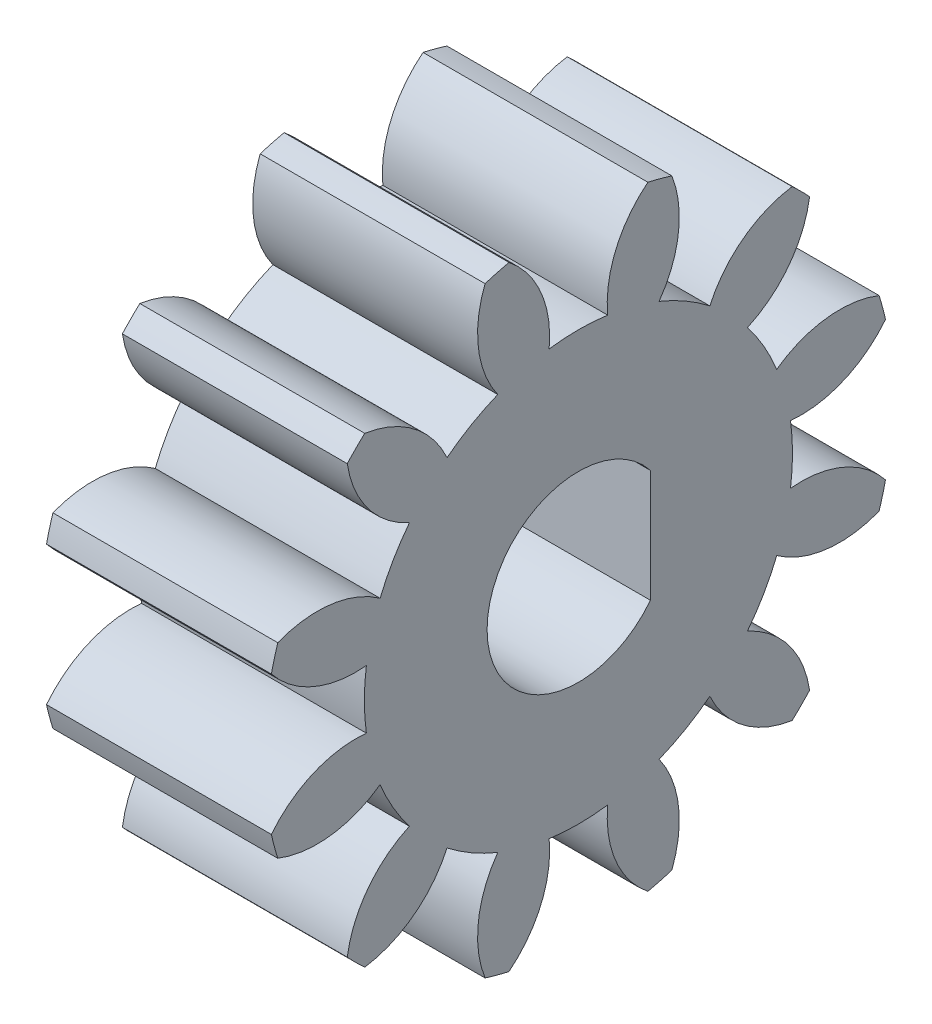
SolidWorks part; units mm, degrees
ref_plane "Plane1" through (0, 0, 0) normal (0, 0, 1) x (1, 0, 0)
ref_plane "Plane2" through (0, 0, 0) normal (0, 1, 0) x (1, 0, 0)
ref_plane "Plane3" through (0, 0, 0) normal (1, 0, 0) x (0, 0, -1)
sketch "HoldingSke" plane through (0, 0, 0) normal (0, 1, 0) x (1, 0, 0)
  line L0 (0, 0) -> (496.899, -105.6191)
  line L1 (-15, 0) -> (100, 0) construction
  line L2 (0, 0) -> (-2.1039, 2.3779)
  line L3 (0, 0) -> (-11.863, 4.5341)
  line L4 (0, 0) -> (8.4473, 1.7955)
  line L5 (0, 0) -> (-47.5972, -17.7524)
  line L6 (0, 0) -> (-5.2639, -3.5516)
  line L7 (-2.1039, 2.3779) -> (8.8308, 51.9871)
  line L8 (-76.2, 54.61) -> (-72.771, 54.61)
  line L9 (-67.7845, 28.3722) -> (-49.3413, 33.142)
  line L10 (-76.2, 71.12) -> (104.1128, 71.12)
  line L11 (0, 0) -> (-6.35, 0)
  line L12 (-76.2, 101.6) -> (-76.1492, 101.6)
  line L13 (24.9733, 27.94) -> (52.9518, 28.4284)
  line L14 (24.9733, 27.94) -> (25.0241, 27.9398)
  line L15 (24.9733, 27.94) -> (100.4021, 29.52)
  circle A0 centre (0, 0) radius 1.5875
  circle A1 centre (0, 0) radius 6.0452
  circle A2 centre (0, 0) radius 38.1
  circle A3 centre (0, 0) radius 1.5875
  dimension "MHD" = 12.0904
  dimension "Hub_dia" = 76.2
  dimension "Bore" = 3.175
  dimension "MBD" = 3.175
  dimension "Num_teeth" = 12
  dimension "Pitch" = 508
  dimension "Overall_len" = 50.8
  dimension "Show_teeth" = 12
  dimension "Thickness" = 6.35
  dimension "OAL" = 50.8001
  dimension "T_dim" = 3.429
  dimension "Ap" = 14.5
  dimension "H" = 19.05
  dimension "Pitch_radius" = 180.3128
  dimension "Width" = 6.35
  dimension "Backlash" = 0.0508
  dimension "Addendum_fac" = 1
  dimension "Dedendum_fac" = 1.2
  dimension "Clearance_fac" = 0.2
  dimension "Dedendum_add" = 0.0508
sketch "BasProSke" plane through (0, 0, 0) normal (0, 1, 0) x (1, 0, 0)
  line L0 (-10, 0) -> (60, 0) construction
  line L1 (0, 0) -> (0, 8.89)
  line L2 (0, 0) -> (6.35, 0)
  line L3 (6.35, 0) -> (6.35, 8.89)
  line L4 (6.35, 8.89) -> (0, 8.89)
  dimension "Thickness" = 6.35
  dimension "Diameter" = 17.78
revolve "Base-Revolve" add sketch "BasProSke" angle 360 about L0
sketch "TooCutSke" plane through (0, 0, 0) normal (1, 0, 0) x (0, 0, -1)
  line L1 (0, 0) -> (0, 107) construction
  line L2 (0, 0) -> (-1.0834, 7.5426) construction
  line L3 (0, 0) -> (-3.9164, 14.6164) construction
  line L4 (-1.0834, 7.5426) -> (-1.9582, 7.3082) construction
  arc A0 (0.8272, 5.9883) -> (-0.8272, 5.9883) centre (0, 0) ccw
  arc A1 (1.9874, 8.6911) -> (-1.9874, 8.6911) centre (0, 0) ccw
  circle A2 centre (0, 0) radius 7.62 construction
  circle A3 centre (0, 0) radius 7.3773 construction
  arc A4 (-0.8272, 5.9883) -> (-1.9874, 8.6911) centre (-3.8605, 6.2865) ccw
  arc A5 (1.9874, 8.6911) -> (0.8272, 5.9883) centre (3.8605, 6.2865) ccw
  dimension "Root_dia" = 12.0904
  dimension "Overcut_dia" = 17.8308
  dimension "Pitch_dia" = 15.24
  dimension "Base_dia" = 14.7546
  dimension "Flank_rad" = 3.048
  dimension "Half_ang" = 15
  dimension "Half_CT" = 0.9057
extrude "ToothCut" cut sketch "TooCutSke" along normal through all
fillet "Breaks" [suppressed] radius 0.0254
fillet "RootFillets" [suppressed] radius 0.3048
pattern_circular "TeethCuts" count 12 every 30 about axis through (-10, 0, 0) along (1, 0, 0) of "ToothCut", "RootFillets", "Breaks"
sketch "HubNeaOneSke" plane through (0, 0, 0) normal (-1, 0, 0) x (0, 0, 1)
  circle A0 centre (0, 0) radius 6.0452
  dimension "Diameter" = 12.0904
extrude "HubNearOne" [suppressed] add sketch "HubNeaOneSke" along normal blind 44.4501
sketch "HubNeaBotSke" plane through (0, 0, 0) normal (-1, 0, 0) x (0, 0, 1)
  circle A0 centre (0, 0) radius 6.0452
  dimension "Diameter" = 12.0904
extrude "HubNearBoth" [suppressed] add sketch "HubNeaBotSke" along normal blind 22.225
ref_plane "FarPln" through (6.35, 0, 0) normal (1, 0, 0) x (0, 0, -1)
sketch "HubFarSke" plane through (6.35, 0, 0) normal (1, 0, 0) x (0, 0, -1)
  circle A0 centre (0, 0) radius 6.0452
  dimension "Diameter" = 12.0904
extrude "HubFar" [suppressed] add sketch "HubFarSke" along normal blind 22.225
sketch "BorSke" plane through (0, 0, 0) normal (1, 0, 0) x (0, 0, -1)
  circle A0 centre (0, 0) radius 1.5875
  dimension "Diameter" = 3.175
extrude "Bore" cut sketch "BorSke" along normal mid plane 101.6001
sketch "KeySke" plane through (0, 0, 0) normal (1, 0, 0) x (0, 0, -1)
  line L0 (-0.127, 0) -> (-0.127, 1.8415)
  line L1 (-0.127, 1.8415) -> (0.127, 1.8415)
  line L2 (0.127, 1.8415) -> (0.127, 0)
  line L3 (0, 0) -> (0, 34) construction
  line L4 (-0.127, 0) -> (0.127, 0)
  dimension "Offset" = 1.8415
  dimension "Width" = 0.254
extrude "Keyway" [suppressed] cut sketch "KeySke" along normal mid plane 101.6001
pattern_circular "Keyway2" [suppressed] count 2 every 90 about axis through (-10, 0, 0) along (1, 0, 0)
sketch "Sketch1" plane through (6.35, 0, 0) normal (1, 0, 0) x (0, 0, -1)
  line L0 (2.5797, 0) -> (3.2579, 0) construction
  line L1 (3.2579, -1.5875) -> (3.2579, 1.5875) construction
  line L2 (3.2579, 1.5875) -> (2.0334, 1.5875) construction
  line L3 (2.0334, 1.5875) -> (2.0334, -1.5875)
  circle A0 centre (0, 0) radius 2.5797
  point P8 (3.2579, 0)
  circle M5 centre (0, 0) radius 1.5875
  dimension "D1" = 5.1594
  dimension "D2" = 3.175
extrude "Cut-Extrude1" cut sketch "Sketch1" against normal through all contours L3 A0 M5
equation "' \"Pitch@HoldingSke\" = 4"
equation "' \"Num_teeth@HoldingSke\" = 12"
equation "' \"Ap@HoldingSke\" =  20"
equation "' \"Ap@HoldingSke\" = 20"
equation "' \"Width@HoldingSke\" = 0.5"
equation "' \"Hub_dia@HoldingSke\"= 1"
equation "' \"Hub_dia@HoldingSke\" = 1"
equation "' \"Overall_len@HoldingSke\" = 1.0"
equation "' \"Bore@HoldingSke\" = 0.75"
equation "' \"T_dim@HoldingSke\" = 0.85"
equation "' \"Width@KeySke\" = 0.25"
equation "' \"Show_teeth@HoldingSke\" = 13"
equation "' \"Backlash@HoldingSke\" = 0.009"
equation "' \"Addendum_fac@HoldingSke\" = 1.0"
equation "' \"Dedendum_fac@HoldingSke\" = 1.25"
equation "' \"Dedendum_add@HoldingSke\" = 0.00005"
equation "' \"Clearance_fac@HoldingSke\" = 0.25"
equation "' \"Pitch@HoldingSke\" = 0.5"
equation "' \"Num_teeth@HoldingSke\" = 23"
equation "' \"Show_teeth@HoldingSke\" = 23"
equation "' \"Backlash@HoldingSke\" = 0.0375"
equation "\"Overcut_dia@TooCutSke\" = (\"Num_teeth@HoldingSke\" + 2 * \"Addendum_fac@HoldingSke\") / \"Pitch@HoldingSke\" + 0.002"
equation "\"Pitch_dia@TooCutSke\" = \"Num_teeth@HoldingSke\" / \"Pitch@HoldingSke\""
equation "\"Base_dia@TooCutSke\" = \"Num_teeth@HoldingSke\" / \"Pitch@HoldingSke\" * cos((\"Ap@HoldingSke\"  * 3.14159265 / 180))"
equation "\"Root_dia@TooCutSke\" = (\"Num_teeth@HoldingSke\" + 2) / \"Pitch@HoldingSke\" - 2 * (\"Addendum_fac@HoldingSke\" + \"Dedendum_fac@HoldingSke\") / \"Pitch@HoldingSke\" - \"Dedendum_add@HoldingSke\" * 2"
equation "\"Half_ang@TooCutSke\" = 180 / \"Num_teeth@HoldingSke\""
equation "\"Half_CT@TooCutSke\" = \"Num_teeth@HoldingSke\" / \"Pitch@HoldingSke\" * sin((3.14159265 / 2 / \"Num_teeth@HoldingSke\")) / 2 - 7 * \"Backlash@HoldingSke\" / 4"
equation "\"Flank_rad@TooCutSke\" = \"Num_teeth@HoldingSke\" / \"Pitch@HoldingSke\" / 5"
equation "\"Radius@RootFillets\" = \"Clearance_fac@HoldingSke\" / \"Pitch@HoldingSke\" + \"Dedendum_add@HoldingSke\""
equation "\"Break_rad@Breaks\" = 0.02 / \"Pitch@HoldingSke\""
equation "\"Thickness@HoldingSke\" = \"Width@HoldingSke\""
equation "\"OAL@HoldingSke\" = \"Thickness@HoldingSke\""
equation "\"MHD@HoldingSke\" = (\"Num_teeth@HoldingSke\" + 2) / \"Pitch@HoldingSke\" - 2 * (\"Addendum_fac@HoldingSke\" + \"Dedendum_fac@HoldingSke\")  / \"Pitch@HoldingSke\" - \"Dedendum_add@HoldingSke\" * 2"
equation "\"MBD@HoldingSke\" = (\"Num_teeth@HoldingSke\" + 2) / \"Pitch@HoldingSke\" - 2 * (\"Addendum_fac@HoldingSke\" + \"Dedendum_fac@HoldingSke\")  / \"Pitch@HoldingSke\" - \"Dedendum_add@HoldingSke\" * 2 - 0.002"
equation "\"MHD@HoldingSke\" = ((sgn( \"MHD@HoldingSke\" - \"Hub_dia@HoldingSke\" )-1)*( \"MHD@HoldingSke\" - \"Hub_dia@HoldingSke\" ))/-2+ \"Hub_dia@HoldingSke\""
equation "\"MBD@HoldingSke\" = ((sgn( \"MBD@HoldingSke\" - \"Bore@HoldingSke\" )-1)*( \"MBD@HoldingSke\" - \"Bore@HoldingSke\" ))/-2+ \"Bore@HoldingSke\""
equation "\"OAL@HoldingSke\" = ((sgn( \"OAL@HoldingSke\" - \"Overall_len@HoldingSke\" )+1)*( \"OAL@HoldingSke\" - \"Overall_len@HoldingSke\" ))/2 + \"Overall_len@HoldingSke\" + 0.000002"
equation "\"Num_teeth@TeethCuts\" = int( \"Show_teeth@HoldingSke\" ) + 1"
equation "\"Num_teeth@TeethCuts\" = ((sgn( \"Num_teeth@TeethCuts\" - \"Num_teeth@HoldingSke\" )-1)*( \"Num_teeth@TeethCuts\" - \"Num_teeth@HoldingSke\" ))/-2+ \"Num_teeth@HoldingSke\""
equation "\"Num_teeth@TeethCuts\" = ((sgn( \"Num_teeth@TeethCuts\" - 2.0)+1)*( \"Num_teeth@TeethCuts\" - 2.0))/2 +2.0"
equation "\"Angle@TeethCuts\" = 360.0 / \"Num_teeth@HoldingSke\""
equation "\"Diameter@BasProSke\" = (\"Num_teeth@HoldingSke\" + 2 * \"Addendum_fac@HoldingSke\") / \"Pitch@HoldingSke\""
equation "\"Thickness@BasProSke\"  = \"Thickness@HoldingSke\""
equation "' \"Fillet_rad@BasProSke\" =  \"Thickness@HoldingSke\" * 0.05"
equation "' \"Fillet_rad@BasProSke\" = \"Thickness@HoldingSke\" * 0.05"
equation "\"MHD@HoldingSke\" = ((sgn( \"MHD@HoldingSke\" - \"Root_dia@TooCutSke\" )-1)*( \"MHD@HoldingSke\" - \"Root_dia@TooCutSke\" ))/-2+ \"Root_dia@TooCutSke\""
equation "\"Diameter@HubNeaOneSke\" = \"MHD@HoldingSke\""
equation "\"Length@HubNearOne\" = \"OAL@HoldingSke\" - \"Thickness@BasProSke\""
equation "\"Diameter@HubNeaBotSke\" = \"MHD@HoldingSke\""
equation "\"Length@HubNearBoth\" = ( \"OAL@HoldingSke\" - \"Thickness@BasProSke\" ) / 2.0"
equation "\"Thickness@FarPln\" = \"Thickness@BasProSke\""
equation "\"Diameter@HubFarSke\" = \"MHD@HoldingSke\""
equation "\"Length@HubFar\" = ( \"OAL@HoldingSke\" - \"Thickness@BasProSke\" ) / 2.0"
equation "\"Diameter@BorSke\" = \"MBD@HoldingSke\""
equation "\"D1@Bore\" = \"OAL@HoldingSke\" * 2.0"
equation "\"D1@Keyway\" = \"OAL@HoldingSke\" * 2.0"
equation "\"Offset@KeySke\" = \"T_dim@HoldingSke\" - \"MBD@HoldingSke\" / 2.0"
